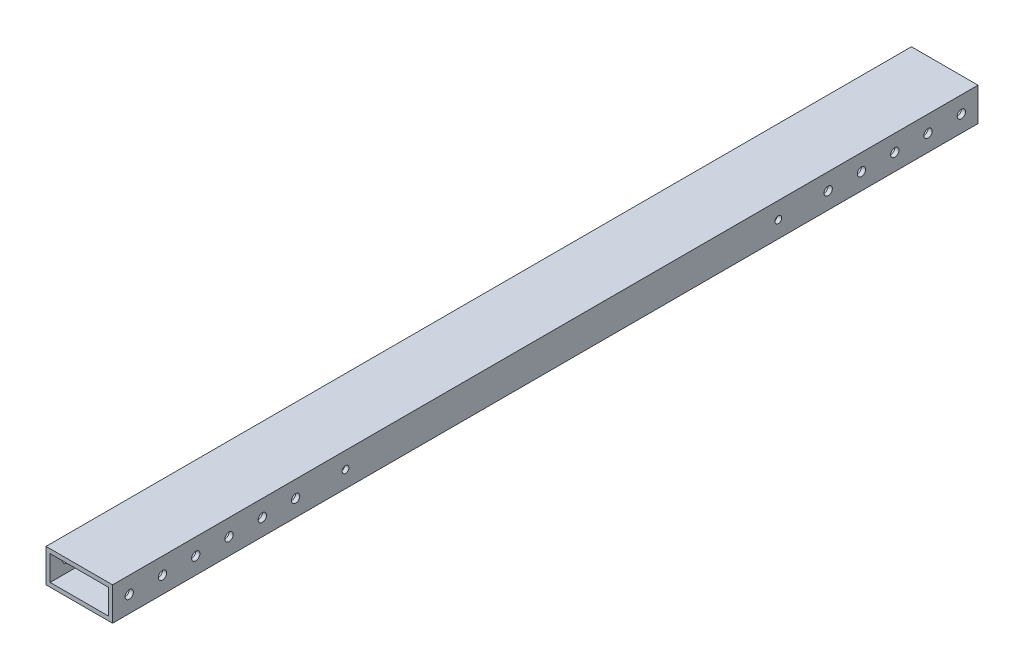
SolidWorks part; units mm, degrees
material "6061 Alloy"
ref_plane "Front Plane" through (0, 0, 0) normal (0, 0, 1) x (1, 0, 0)
ref_plane "Top Plane" through (0, 0, 0) normal (0, 1, 0) x (1, 0, 0)
ref_plane "Right Plane" through (0, 0, 0) normal (1, 0, 0) x (0, 0, -1)
sketch "Sketch1" plane through (0, 0, 0) normal (0, 0, 1) x (1, 0, 0)
  line L0 (-22.225, 9.525) -> (22.225, 9.525)
  line L2 (-25.4, 12.7) -> (25.4, 12.7)
  line L3 (-25.4, 12.7) -> (-25.4, -12.7)
  line L4 (-25.4, -12.7) -> (25.4, -12.7)
  line L5 (25.4, 12.7) -> (25.4, -12.7)
  line L10 (22.225, 9.525) -> (22.225, -9.525)
  line L11 (-22.225, -9.525) -> (22.225, -9.525)
  line L12 (-22.225, 9.525) -> (-22.225, -9.525)
  point P12 (0, 12.7)
  point P14 (25.4, 0)
  dimension "Wall Thickness" = 3.175
  dimension "Outside Width" = 50.8
  dimension "Outside Height" = 25.4
  dimension "Inside Height" = 19.05
  dimension "Inside Width" = 44.45
sketch "Sketch2" plane through (0, 0, 0) normal (1, 0, 0) x (0, 0, -1)
  line L0 (330.2, 0) -> (-330.2, 0)
  point P4 (0, 0)
  point P7 (-330.2, 0)
  point P10 (330.2, 0)
  dimension "Length" = 660.4
sketch "Sketch3" plane through (0, 0, 0) normal (0, 0, 1) x (1, 0, 0)
  line L21 (25.4, 12.7) -> (-25.4, 12.7)
  line L22 (25.4, -12.7) -> (25.4, 12.7)
  line L23 (-25.4, -12.7) -> (25.4, -12.7)
  line L24 (-25.4, 12.7) -> (-25.4, -12.7)
  line L25 (25.4, 12.7) -> (-25.4, 12.7)
  line L26 (25.4, -12.7) -> (25.4, 12.7)
  line L27 (-25.4, -12.7) -> (25.4, -12.7)
  line L28 (-25.4, 12.7) -> (-25.4, -12.7)
  line L29 (22.225, 9.525) -> (-22.225, 9.525)
  line L30 (22.225, -9.525) -> (22.225, 9.525)
  line L31 (-22.225, -9.525) -> (22.225, -9.525)
  line L32 (-22.225, 9.525) -> (-22.225, -9.525)
  line L33 (22.225, 9.525) -> (-22.225, 9.525)
  line L34 (22.225, -9.525) -> (22.225, 9.525)
  line L35 (-22.225, -9.525) -> (22.225, -9.525)
  line L36 (-22.225, 9.525) -> (-22.225, -9.525)
  dimension "D1" = 0
  dimension "D2" = 0
extrude "Boss-Extrude1" add sketch "Sketch3" along normal up to vertex (330.2 mm away) and the other way up to vertex (330.2 mm away) up to point (0, 0, 330.2) other way up to point (0, 0, -330.2)
sketch "Drawing Reference" plane through (0, 0, 0) normal (1, 0, 0) x (0, 0, -1)
  line L0 (-330.2, 0) -> (330.2, 0) construction
  line L1 (0, -12.7) -> (0, 12.7) construction
  line L2 (-330.2, -12.7) -> (330.2, -12.7) construction
  line L5 (-330.2, 12.7) -> (330.2, 12.7) construction
  point P7 (-293.624, 0)
  point P8 (293.624, 0)
  dimension "D1" = 36.576
sketch "Sketch5" plane through (25.4, 0, 0) normal (1, 0, 0) x (0, 0, -1)
  line L2 (-266.7, 0) -> (-241.3, 0)
  line L3 (-241.3, 0) -> (-215.9, 0)
  line L4 (-215.9, 0) -> (-190.5, 0)
  line L5 (-317.5, 0) -> (-330.2, 0)
  line L6 (-330.2, -12.7) -> (-330.2, 12.7) construction
  line L7 (-317.5, 0) -> (-292.1, 0)
  line L8 (-292.1, 0) -> (-266.7, 0)
sketch "Sketch8" plane through (25.4, 0, 0) normal (1, 0, 0) x (0, 0, -1)
  line L0 (330.2, 0) -> (292.1, 0)
  line L1 (330.2, -12.7) -> (330.2, 12.7) construction
  line L2 (292.1, 0) -> (266.7, 0)
  line L3 (266.7, 0) -> (241.3, 0)
  line L4 (241.3, 0) -> (215.9, 0)
  line L5 (330.2, 0) -> (317.5, 0)
hole_wizard "1/4 (0.25) Diameter Hole3" positions "Sketch12" profile "Sketch13" hole size "1/4" standard "ANSI Inch" end condition through all
sketch "Sketch12" plane through (-25.4, 0, 0) normal (-1, 0, 0) x (0, 0, 1)
  point P4 (-317.5, 0)
sketch "Sketch13" plane through (-25.4, 0, -317.5) normal (0, 1, 0) x (0, 0, 1)
  line L0 (0, 0) -> (0, 50.8)
  line L1 (0, 50.8) -> (3.175, 50.8)
  line L2 (3.175, 50.8) -> (3.175, 0)
  line L5 (3.175, 0) -> (0, 0)
  line L11 (0, -6.35) -> (0, 107.95) construction
  dimension "Thru Hole Dia." = 6.35
  dimension "Thru Hole Depth" = 50.8
hole_wizard "1/4 (0.25) Diameter Hole4" positions "Sketch14" profile "Sketch15" hole size "1/4" standard "ANSI Inch" end condition through all
sketch "Sketch14" plane through (-25.4, 0, 0) normal (-1, 0, 0) x (0, 0, 1)
  point P0 (292.1, 0)
  point P3 (317.5, 0)
sketch "Sketch15" plane through (-25.4, 0, 292.1) normal (0, 1, 0) x (0, 0, 1)
  line L0 (0, 0) -> (0, 50.8)
  line L1 (0, 50.8) -> (3.175, 50.8)
  line L2 (3.175, 50.8) -> (3.175, 0)
  line L5 (3.175, 0) -> (0, 0)
  line L11 (0, -6.35) -> (0, 107.95) construction
  dimension "Thru Hole Dia." = 6.35
  dimension "Thru Hole Depth" = 50.8
hole_wizard "1/4 (0.25) Diameter Hole5" positions "Sketch17" profile "Sketch18" hole size "1/4" standard "ANSI Inch" end condition through all
sketch "Sketch17" plane through (25.4, 0, 0) normal (1, 0, 0) x (0, 0, -1)
  point P0 (292.1, 0)
  point P3 (266.7, 0)
sketch "Sketch18" plane through (25.4, 0, -292.1) normal (0, 1, 0) x (0, 0, -1)
  line L0 (0, 0) -> (0, 50.8)
  line L1 (0, 50.8) -> (3.175, 50.8)
  line L2 (3.175, 50.8) -> (3.175, 0)
  line L5 (3.175, 0) -> (0, 0)
  line L11 (0, -6.35) -> (0, 107.95) construction
  dimension "Thru Hole Dia." = 6.35
  dimension "Thru Hole Depth" = 50.8
hole_wizard "1/4 (0.25) Diameter Hole6" positions "Sketch19" profile "Sketch20" hole size "1/4" standard "ANSI Inch" end condition through all
sketch "Sketch19" plane through (25.4, 0, 0) normal (1, 0, 0) x (0, 0, -1)
  point P0 (215.9, 0)
  point P3 (241.3, 0)
sketch "Sketch20" plane through (25.4, 0, -215.9) normal (0, 1, 0) x (0, 0, -1)
  line L0 (0, 0) -> (0, 50.8)
  line L1 (0, 50.8) -> (3.175, 50.8)
  line L2 (3.175, 50.8) -> (3.175, 0)
  line L5 (3.175, 0) -> (0, 0)
  line L11 (0, -6.35) -> (0, 107.95) construction
  dimension "Thru Hole Dia." = 6.35
  dimension "Thru Hole Depth" = 50.8
hole_wizard "1/4 (0.25) Diameter Hole7" positions "Sketch21" profile "Sketch22" hole size "1/4" standard "ANSI Inch" end condition through all
sketch "Sketch21" plane through (25.4, 0, 0) normal (1, 0, 0) x (0, 0, -1)
  point P0 (-190.5, 0)
  point P3 (-215.9, 0)
sketch "Sketch22" plane through (25.4, 0, 190.5) normal (0, 1, 0) x (0, 0, -1)
  line L0 (0, 0) -> (0, 50.8)
  line L1 (0, 50.8) -> (3.175, 50.8)
  line L2 (3.175, 50.8) -> (3.175, 0)
  line L5 (3.175, 0) -> (0, 0)
  line L11 (0, -6.35) -> (0, 107.95) construction
  dimension "Thru Hole Dia." = 6.35
  dimension "Thru Hole Depth" = 50.8
hole_wizard "1/4 (0.25) Diameter Hole8" positions "Sketch23" profile "Sketch24" hole size "1/4" standard "ANSI Inch" end condition through all
sketch "Sketch23" plane through (25.4, 0, 0) normal (1, 0, 0) x (0, 0, -1)
  point P0 (-266.7, 0)
  point P3 (-241.3, 0)
sketch "Sketch24" plane through (25.4, 0, 266.7) normal (0, 1, 0) x (0, 0, -1)
  line L0 (0, 0) -> (0, 50.8)
  line L1 (0, 50.8) -> (3.175, 50.8)
  line L2 (3.175, 50.8) -> (3.175, 0)
  line L5 (3.175, 0) -> (0, 0)
  line L11 (0, -6.35) -> (0, 107.95) construction
  dimension "Thru Hole Dia." = 6.35
  dimension "Thru Hole Depth" = 50.8
sketch "Sketch25" plane through (25.4, 0, 0) normal (1, 0, 0) x (0, 0, -1)
  line L0 (-190.5, 0) -> (-152.4, 0)
  line L1 (215.9, 0) -> (177.8, 0)
hole_wizard "13/64 (0.20313) Diameter Hole1" positions "Sketch26" profile "Sketch27" hole size "13/64" standard "ANSI Inch" end condition through all
sketch "Sketch26" plane through (25.4, 0, 0) normal (1, 0, 0) x (0, 0, -1)
  point P0 (-152.4, 0)
  point P3 (177.8, 0)
sketch "Sketch27" plane through (25.4, 0, 152.4) normal (0, 1, 0) x (0, 0, -1)
  line L0 (0, 0) -> (0, 50.8)
  line L1 (0, 50.8) -> (2.5798, 50.8)
  line L2 (2.5798, 50.8) -> (2.5798, 0)
  line L5 (2.5798, 0) -> (0, 0)
  line L11 (0, -6.35) -> (0, 107.95) construction
  dimension "Thru Hole Dia." = 5.1595
  dimension "Thru Hole Depth" = 50.8
hole_wizard "1/2 (0.5) Diameter Hole1" positions "Sketch33" profile "Sketch34" hole size "1/2" standard "ANSI Inch"
sketch "Sketch33" plane through (-25.4, 0, 0) normal (-1, 0, 0) x (0, 0, 1)
  point P0 (-146.05, 0)
  point P3 (120.65, 0)
  point P12 (101.6, 0)
  point P14 (76.2, 0)
sketch "Sketch34" plane through (-25.4, 0, -146.05) normal (0, 1, 0) x (0, 0, 1)
  line L0 (0, 0) -> (0, 10.1655)
  line L1 (0, 10.1655) -> (6.35, 6.35)
  line L2 (6.35, 6.35) -> (6.35, 0)
  line L5 (6.35, 0) -> (0, 0)
  line L10 (0, 10.1655) -> (-6.35, 6.35) construction
  line L11 (0, -6.35) -> (0, 107.95) construction
  dimension "Hole Dia." = 12.7
  dimension "Hole Depth" = 6.35
  dimension "Drill Angle" = 118
equation "\"D1@Drawing Reference\"=\"Outside Width@Sketch1\" * 0.72"
